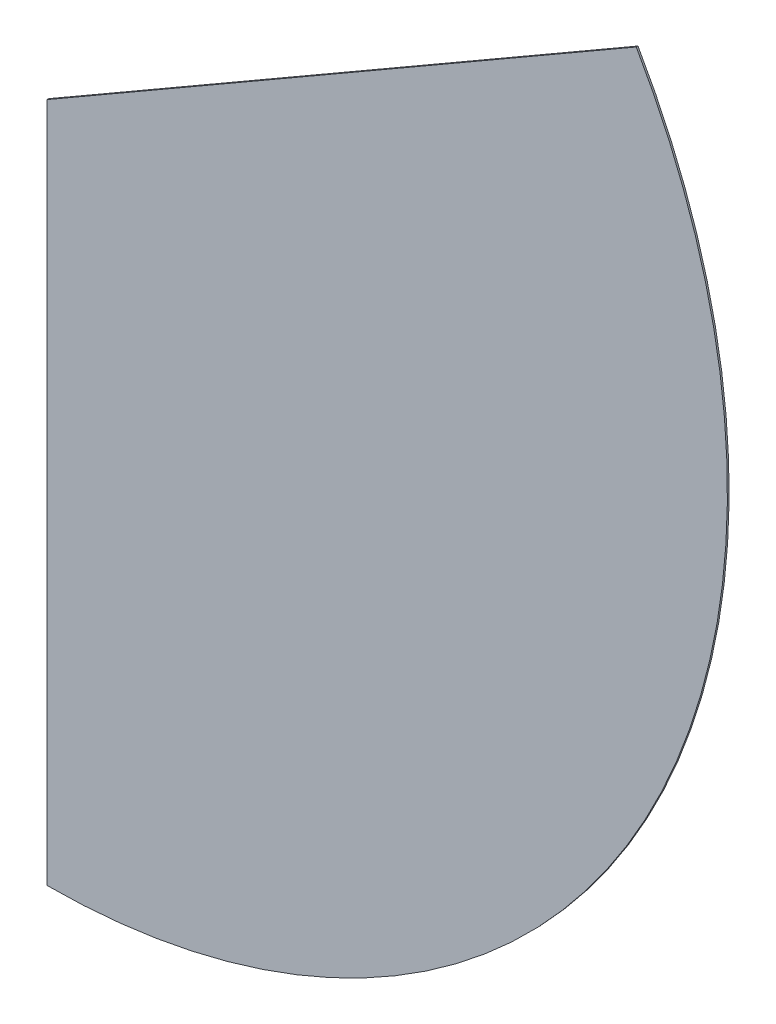
SolidWorks part; units mm, degrees
ref_plane "前基準面" through (0, 0, 0) normal (0, 0, 1) x (1, 0, 0)
ref_plane "上基準面" through (0, 0, 0) normal (0, 1, 0) x (1, 0, 0)
ref_plane "右基準面" through (0, 0, 0) normal (1, 0, 0) x (0, 0, -1)
sketch "草圖1" plane through (0, 0, 0) normal (0, 0, 1) x (1, 0, 0)
  line L0 (0, 0) -> (134.2339, 77.5)
  line L1 (0, 0) -> (0, -155)
  arc A0 (134.2339, 77.5) -> (0, -155) centre (0, 0) cw
  dimension "D2" = 155
  dimension "D1" = 120
extrude "Board" add sketch "草圖1" along normal blind 0.3912
